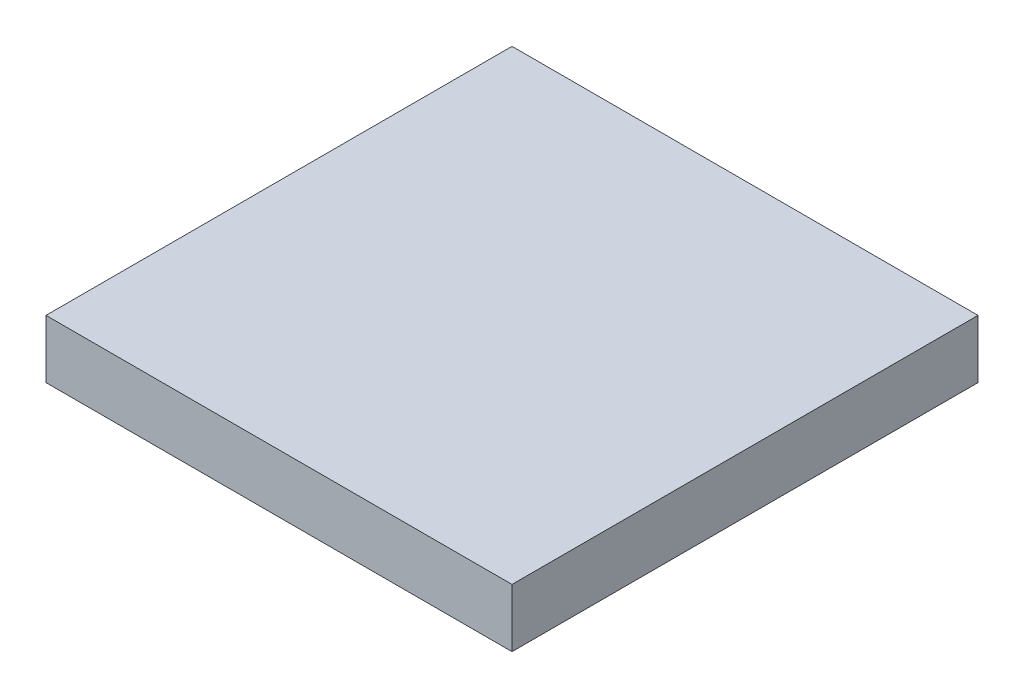
SolidWorks part; units mm, degrees
material "Rubber"
ref_plane "Front Plane" through (0, 0, 0) normal (0, 0, 1) x (1, 0, 0)
ref_plane "Top Plane" through (0, 0, 0) normal (0, 1, 0) x (1, 0, 0)
ref_plane "Right Plane" through (0, 0, 0) normal (1, 0, 0) x (0, 0, -1)
sketch "Sketch1" plane through (0, 0, 0) normal (0, 0, 1) x (1, 0, 0)
  line L1 (12.7, -15.875) -> (-12.7, -15.875)
  line L2 (12.7, -15.875) -> (12.7, -12.7)
  line L3 (12.7, -12.7) -> (-12.7, -12.7)
  line L4 (-12.7, -15.875) -> (-12.7, -12.7)
  line L5 (12.7, -15.875) -> (-12.7, -12.7) construction
  line L6 (12.7, -12.7) -> (-12.7, -15.875) construction
  point P0 (0, -14.2875)
  dimension "D1" = 3.175
  dimension "D2" = 12.7
  dimension "D3" = 25.4
extrude "Boss-Extrude1" add sketch "Sketch1" along normal mid plane 25.4
